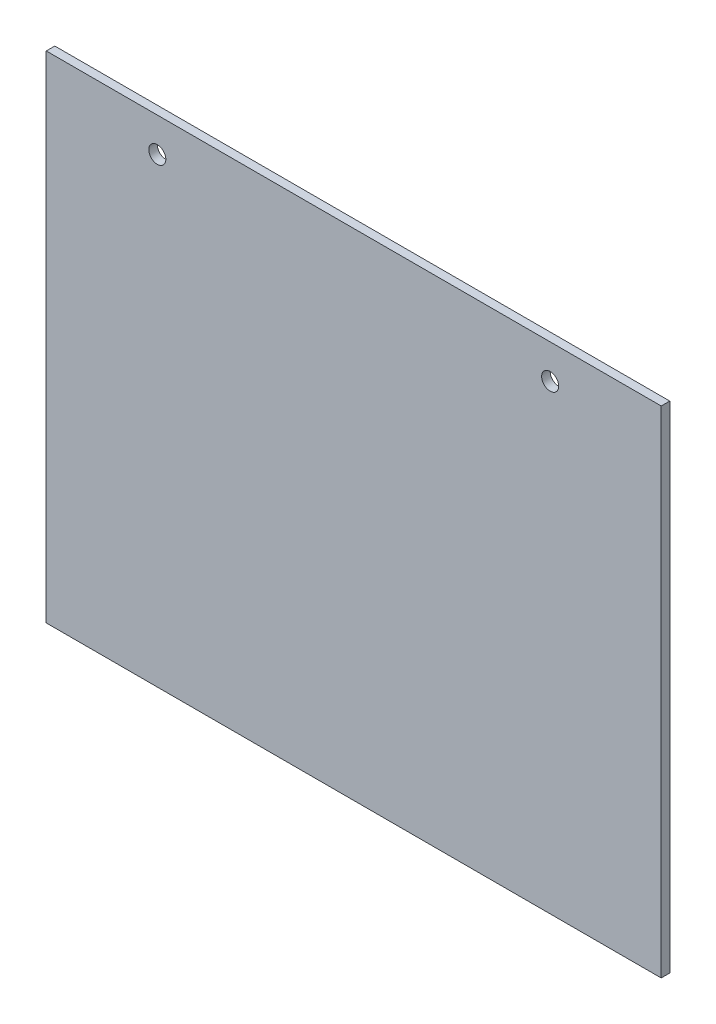
SolidWorks part; units mm, degrees
material "Papel canelado"
ref_plane "Plano frontal" through (0, 0, 0) normal (0, 0, 1) x (1, 0, 0)
ref_plane "Plano superior" through (0, 0, 0) normal (0, 1, 0) x (1, 0, 0)
ref_plane "Plano direito" through (0, 0, 0) normal (1, 0, 0) x (0, 0, -1)
sketch "Esboço1" plane through (0, 0, 0) normal (0, 0, 1) x (1, 0, 0)
  line L1 (0, 0) -> (360, 0)
  line L2 (0, 0) -> (0, 290)
  line L3 (0, 290) -> (360, 290)
  line L4 (360, 0) -> (360, 290)
  dimension "D1" = 360
  dimension "D2" = 290
extrude "Ressalto-extrusão1" add sketch "Esboço1" along normal blind 5
sketch "Esboço2" plane through (0, 0, 5) normal (0, 0, 1) x (1, 0, 0)
  line L0 (360, 290) -> (0, 290) construction
  line L1 (0, 270) -> (65, 270) construction
  line L2 (0, 290) -> (0, 0) construction
  line L3 (295, 270) -> (360, 270) construction
  line L4 (360, 0) -> (360, 290) construction
  circle A0 centre (65, 270) radius 5
  circle A1 centre (295, 270) radius 5
  dimension "D1" = 20
  dimension "D2" = 230
  dimension "D3" = 10
extrude "Corte-extrusão1" cut sketch "Esboço2" against normal through all
